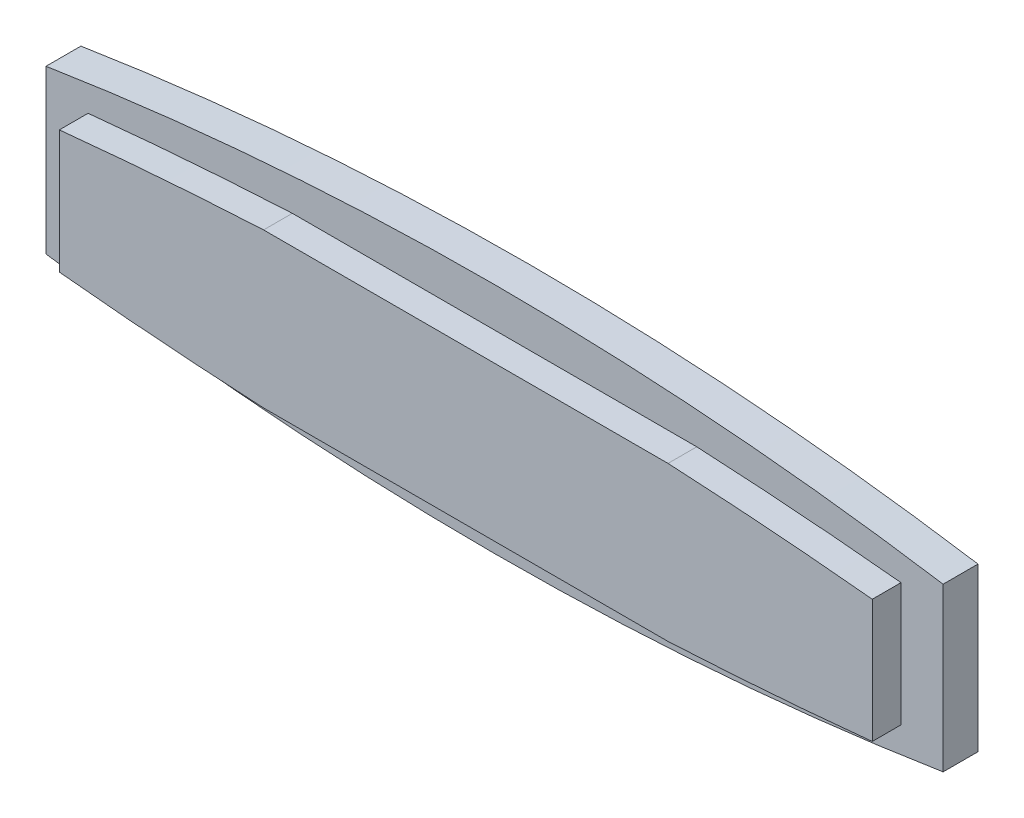
SolidWorks part; units mm, degrees
ref_plane "Спереди" through (0, 0, 0) normal (0, 0, 1) x (1, 0, 0)
ref_plane "Сверху" through (0, 0, 0) normal (0, 1, 0) x (1, 0, 0)
ref_plane "Справа" through (0, 0, 0) normal (1, 0, 0) x (0, 0, -1)
sketch "Эскиз1" plane through (0, 0, 0) normal (0, 0, 1) x (1, 0, 0)
  line L1 (-21.85, 5.675) -> (21.85, 5.675)
  line L2 (-21.85, 5.675) -> (-21.85, -5.675)
  line L3 (-21.85, -5.675) -> (21.85, -5.675)
  line L4 (21.85, 5.675) -> (21.85, -5.675)
  line L5 (-21.85, 5.675) -> (21.85, -5.675) construction
  line L6 (-21.85, -5.675) -> (21.85, 5.675) construction
  point P0 (0, 0)
  dimension "D1" = 43.7
  dimension "D2" = 11.35
extrude "Вытянуть1" add sketch "Эскиз1" along normal blind 1.7
sketch "Эскиз2" plane through (0, 0, 1.7) normal (0, 0, 1) x (1, 0, 0)
  line L0 (21.85, 5.675) -> (-21.85, 5.675) construction
  line L1 (-21.85, -5.675) -> (21.85, -5.675) construction
  arc A0 (39.4562, 0) -> (-39.4562, 0) centre (0, -134.325) ccw
  arc A1 (-39.4562, 0) -> (39.4562, 0) centre (0, 134.325) ccw
  dimension "D1" = 280
extrude "Вытянуть3" cut sketch "Эскиз2" against normal through all flip side to cut
sketch "Эскиз3" plane through (0, 0, 1.7) normal (0, 0, 1) x (1, 0, 0)
  line L0 (-9.85, 3.755) -> (9.85, 3.755)
  line L1 (0, 5.675) -> (0, -5.675) construction
  line L2 (-19.8, -3) -> (19.8, 3) construction
  line L3 (-21.85, 0) -> (21.85, 0) construction
  line L4 (-21.85, 3.9594) -> (-21.85, -3.9594) construction
  line L5 (21.85, -3.9594) -> (21.85, 3.9594) construction
  line L6 (-19.8, 3) -> (-19.8, -3)
  line L7 (19.8, -3) -> (19.8, 3)
  line L8 (-9.85, -3.755) -> (9.85, -3.755)
  arc A0 (-9.85, 3.755) -> (-19.8, 3) centre (0, -191.9973) ccw
  arc A1 (19.8, -3) -> (9.85, -3.755) centre (0, 191.9973) cw
  arc A2 (21.85, 3.9594) -> (-21.85, 3.9594) centre (0, -134.325) ccw construction
  arc A3 (-21.85, -3.9594) -> (21.85, -3.9594) centre (0, 134.325) ccw construction
  arc A4 (-9.85, -3.755) -> (-19.8, -3) centre (0, 191.9973) cw
  arc A7 (19.8, 3) -> (9.85, 3.755) centre (0, -191.9973) ccw
  dimension "D2" = 196
  dimension "D1" = 39.6
  dimension "D3" = 19.7
  dimension "D4" = 6
extrude "Вытянуть4" add sketch "Эскиз3" along normal blind 1.4
